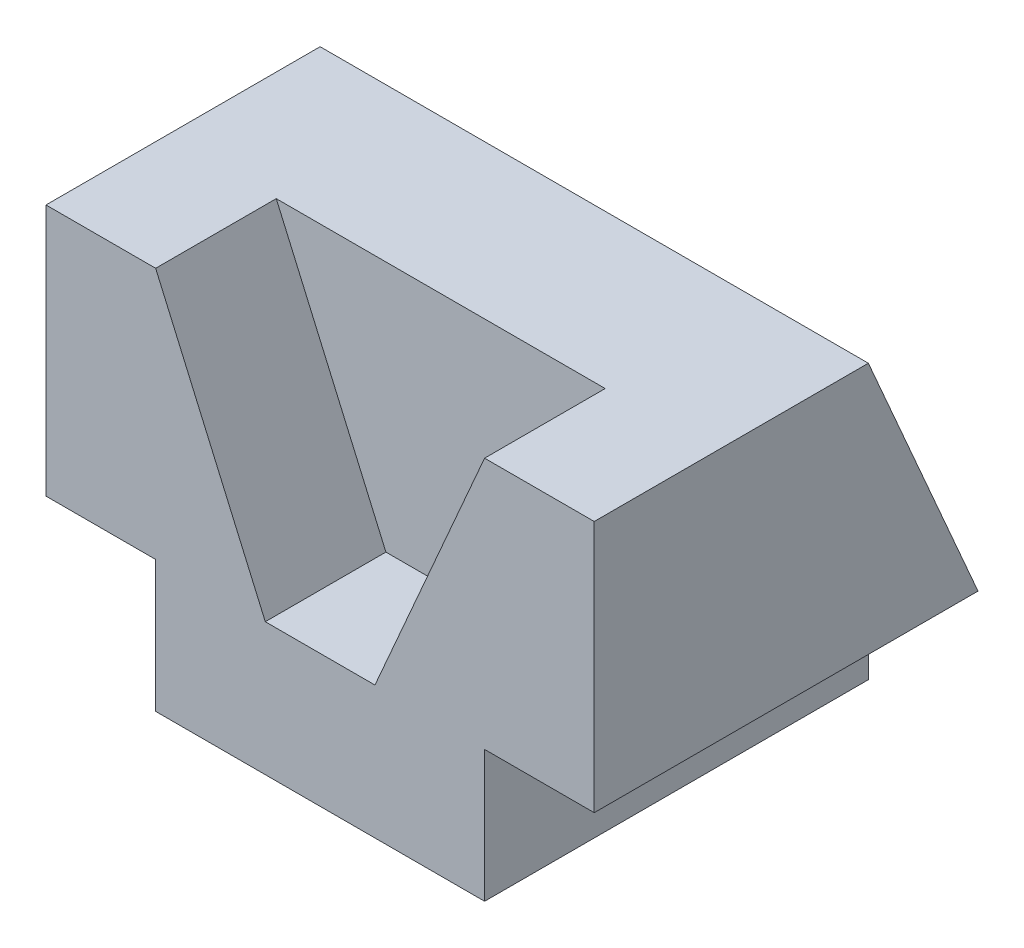
SolidWorks part; units mm, degrees
ref_plane "Front Plane" through (0, 0, 0) normal (0, 0, 1) x (1, 0, 0)
ref_plane "Top Plane" through (0, 0, 0) normal (0, 1, 0) x (1, 0, 0)
ref_plane "Right Plane" through (0, 0, 0) normal (1, 0, 0) x (0, 0, -1)
sketch "Sketch3" plane through (0, 0, 0) normal (0, 0, 1) x (1, 0, 0)
  line L0 (-15000, 0) -> (15000, 0)
  line L1 (15000, 0) -> (15000, 12000)
  line L2 (15000, 12000) -> (25000, 12000)
  line L3 (25000, 12000) -> (25000, 35000)
  line L4 (25000, 35000) -> (-25000, 35000)
  line L5 (-25000, 35000) -> (-25000, 12000)
  line L6 (-25000, 12000) -> (-15000, 12000)
  line L7 (-15000, 12000) -> (-15000, 0)
  line L8 (0, 45342.2345) -> (0, -20659.756) construction
  dimension "D1" = 15000
  dimension "D2" = 30000
  dimension "D3" = 25000
  dimension "D4" = 50000
  dimension "D5" = 12000
  dimension "D6" = 12000
  dimension "D7" = 23000
extrude "Boss-Extrude2" add sketch "Sketch3" along normal blind 35000
sketch "Sketch4" plane through (0, 0, 35000) normal (0, 0, 1) x (1, 0, 0)
  line L0 (0, -4689.9201) -> (0, 38308.4465) construction
  line L1 (-5000, 12082.0815) -> (-15000, 35000)
  line L2 (-15000, 35000) -> (15000, 35000)
  line L3 (25000, 35000) -> (-25000, 35000) construction
  line L4 (15000, 35000) -> (5000, 12082.0815)
  line L5 (5000, 12082.0815) -> (-5000, 12082.0815)
  dimension "D1" = 5000
  dimension "D2" = 10000
  dimension "D3" = 10000
  dimension "D4" = 10000
extrude "Cut-Extrude1" cut sketch "Sketch4" against normal blind 11000
sketch "Sketch6" plane through (-25000, 0, 0) normal (-1, 0, 0) x (0, 0, 1)
  line L0 (0, 12000) -> (10000, 35000)
  line L1 (35000, 35000) -> (0, 35000) construction
  line L2 (10000, 35000) -> (0, 35000)
  line L3 (0, 35000) -> (0, 12000)
  line L4 (0, 12000) -> (-176.7677, 11790.2476)
  line M2 (0, 35000) -> (0, 12000)
  line M5 (35000, 35000) -> (0, 35000)
  dimension "D1" = 10000
extrude "Cut-Extrude2" cut sketch "Sketch6" against normal through all contours L0 M2 M5
